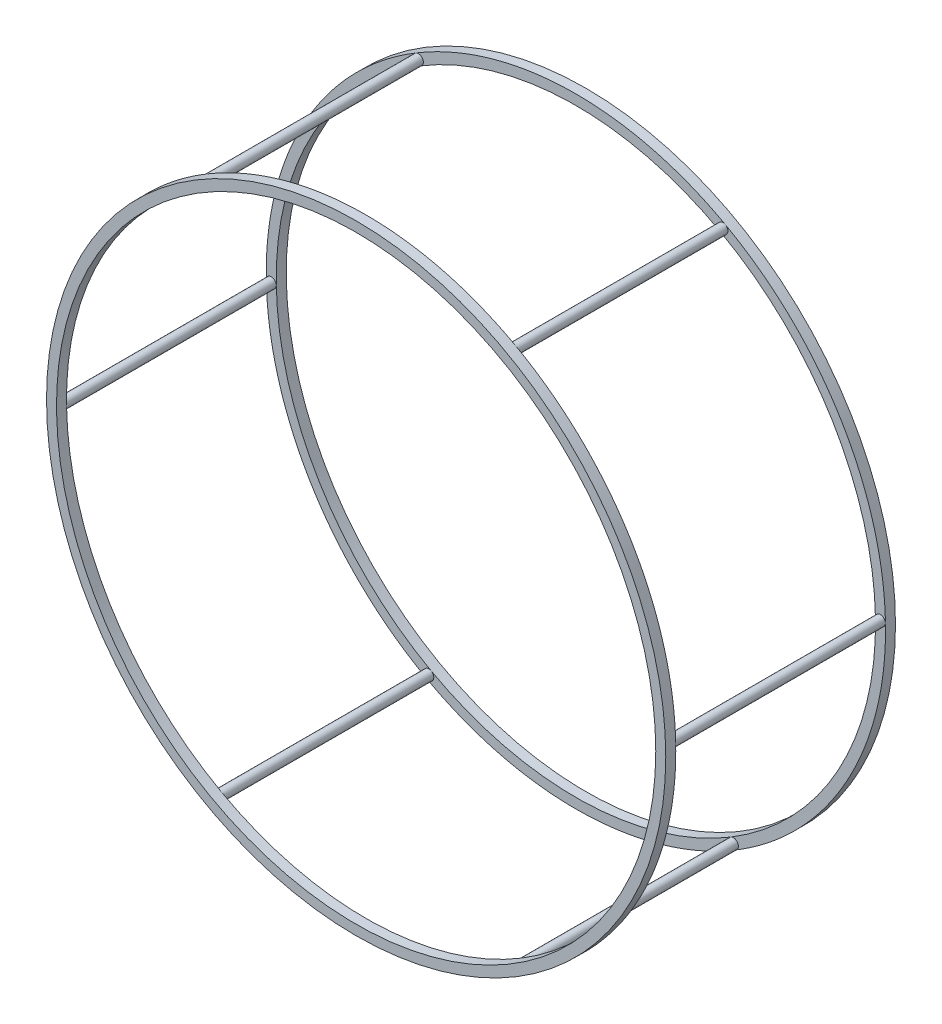
SolidWorks part; units mm, degrees
ref_plane "Front Plane" through (0, 0, 0) normal (0, 0, 1) x (1, 0, 0)
ref_plane "Top Plane" through (0, 0, 0) normal (0, 1, 0) x (1, 0, 0)
ref_plane "Right Plane" through (0, 0, 0) normal (1, 0, 0) x (0, 0, -1)
sketch "Sketch1" plane through (0, 0, 0) normal (0, 0, 1) x (1, 0, 0)
  circle A0 centre (0, 0) radius 150
  circle A1 centre (0, 0) radius 155
  dimension "D1" = 300
  dimension "D2" = 5
extrude "Boss-Extrude1" add sketch "Sketch1" along normal blind 115
sketch "Sketch2" plane through (0, 0, 0) normal (1, 0, 0) x (0, 0, -1)
  line L0 (0, 155) -> (-115, 155) construction
  line L1 (-5, -155) -> (-110, -155)
  line L2 (-5, -155) -> (-5, 155)
  line L3 (-5, 155) -> (-110, 155)
  line L4 (-110, -155) -> (-110, 155)
  line L5 (-5, -155) -> (-110, 155) construction
  line L6 (-5, 155) -> (-110, -155) construction
  line L7 (-115, 155) -> (-115, -155) construction
  line L8 (0, -155) -> (0, 155) construction
  line L9 (-115, -155) -> (0, -155) construction
  point P0 (-57.5, 0)
  dimension "D1" = 5
  dimension "D2" = 5
extrude "Cut-Extrude1" cut sketch "Sketch2" against normal through all both and the other way through all
sketch "Sketch3" plane through (0, 0, 110) normal (0, 0, -1) x (-1, 0, 0)
  line L0 (0, -1000) -> (0, 49000) construction
  line L1 (77.5958, 128.3701) -> (80.0963, 132.7011) construction
  circle A0 centre (0, 0) radius 150 construction
  circle A1 centre (0, 0) radius 155 construction
  circle A2 centre (78.8461, 130.5356) radius 2.5
  dimension "D1" = 30
extrude "Boss-Extrude2" add sketch "Sketch3" along normal up to surface (105 mm away) up to face at (0, 150, 5)
pattern_circular "CirPattern2" count 6 over 360 about axis through (0, 0, 0) along (0, 0, 1) of "Boss-Extrude2"
ref_plane "Plane1" through (0, 0, 2.5) normal (0, 0, -1) x (-1, 0, 0)
sketch "Sketch6" plane through (0, 0, 2.5) normal (0, 0, -1) x (-1, 0, 0)
  circle A0 centre (0, 0) radius 155 construction
  circle A1 centre (0, 0) radius 155
